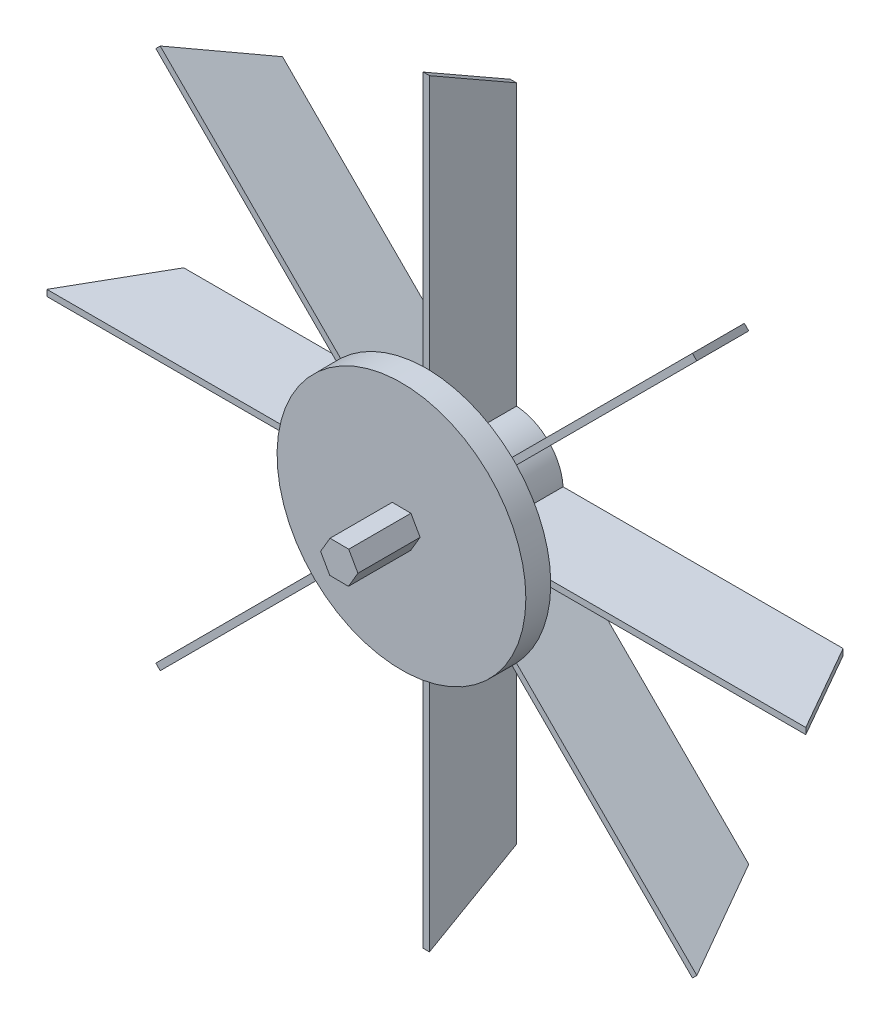
SolidWorks part; units mm, degrees
ref_plane "Front Plane" through (0, 0, 0) normal (0, 0, 1) x (1, 0, 0)
ref_plane "Top Plane" through (0, 0, 0) normal (0, 1, 0) x (1, 0, 0)
ref_plane "Right Plane" through (0, 0, 0) normal (1, 0, 0) x (0, 0, -1)
sketch "Sketch1" plane through (0, 0, 0) normal (0, 0, 1) x (1, 0, 0)
  line L1 (-0.7387, 1.3055) -> (-1.4999, 0.013)
  line L2 (-1.4999, 0.013) -> (-0.7612, -1.2925)
  line L3 (-0.7612, -1.2925) -> (0.7387, -1.3055)
  line L4 (0.7387, -1.3055) -> (1.4999, -0.013)
  line L5 (1.4999, -0.013) -> (0.7612, 1.2925)
  line L6 (0.7612, 1.2925) -> (-0.7387, 1.3055)
  circle A0 centre (0, 0) radius 1.299 construction
  dimension "D1" = 1.5
extrude "Boss-Extrude1" add sketch "Sketch1" along normal blind 5
sketch "Sketch2" plane through (0, 0, 0) normal (0, 0, 1) x (1, 0, 0)
  circle A0 centre (0, 0) radius 10
  dimension "D1" = 20
extrude "Boss-Extrude2" add sketch "Sketch2" along normal blind 2
sketch "Sketch4" plane through (0, 0, 0) normal (0, 0, 1) x (1, 0, 0)
  circle A0 centre (0, 0) radius 4
  circle A1 centre (0, 0) radius 3
  dimension "D1" = 8
  dimension "D2" = 1
extrude "Boss-Extrude3" add sketch "Sketch4" against normal blind 7
sketch "Sketch7" plane through (0, 0, 0) normal (1, 0, 0) x (0, 0, -1)
  line L0 (7, 4) -> (7, 3) construction
  line L1 (7, 3.5) -> (0, 3.5)
  line L3 (0, 3.5) -> (0, 30.5)
  line L4 (7, 3.5) -> (7, 26.5)
  line L5 (7, 26.5) -> (0, 30.5)
  line L6 (0, -10) -> (0, 10) construction
  dimension "D1" = 27
  dimension "D2" = 23
extrude "Boss-Extrude5" add sketch "Sketch7" along normal mid plane 0.5
sketch "Sketch8" plane through (0, 0, 0) normal (1, 0, 0) x (0, 0, -1)
  line L0 (-7.4021, 0) -> (6.5459, 0) construction
pattern_circular "CirPattern1" count 8 over 360 about axis through (0, 0, 0) along (0, 0, 1) of "Boss-Extrude5"
ref_plane "Plane1" through (-1.4999, 0.013, 5) normal (0, 0, -1) x (-1, 0, 0)
sketch "Sketch9" plane through (-1.4999, 0.013, 5) normal (0, 0, -1) x (-1, 0, 0)
  line L6 (-0.7612, 1.2925) -> (-2.2612, 1.2795)
  line L7 (0, 0) -> (-0.7612, 1.2925)
  line L8 (-0.7387, -1.3055) -> (0, 0)
  line L9 (-2.2387, -1.3185) -> (-0.7387, -1.3055)
  line L10 (-2.9999, -0.026) -> (-2.2387, -1.3185)
  line L11 (-2.2612, 1.2795) -> (-2.9999, -0.026)
  line L12 (-0.7612, 1.2925) -> (-2.2612, 1.2795)
  line L13 (0, 0) -> (-0.7612, 1.2925)
  line L14 (-0.7387, -1.3055) -> (0, 0)
  line L15 (-2.2387, -1.3185) -> (-0.7387, -1.3055)
  line L16 (-2.9999, -0.026) -> (-2.2387, -1.3185)
  line L17 (-2.2612, 1.2795) -> (-2.9999, -0.026)
  dimension "D1" = 0
extrude "Boss-Extrude6" add sketch "Sketch9" against normal blind 2
